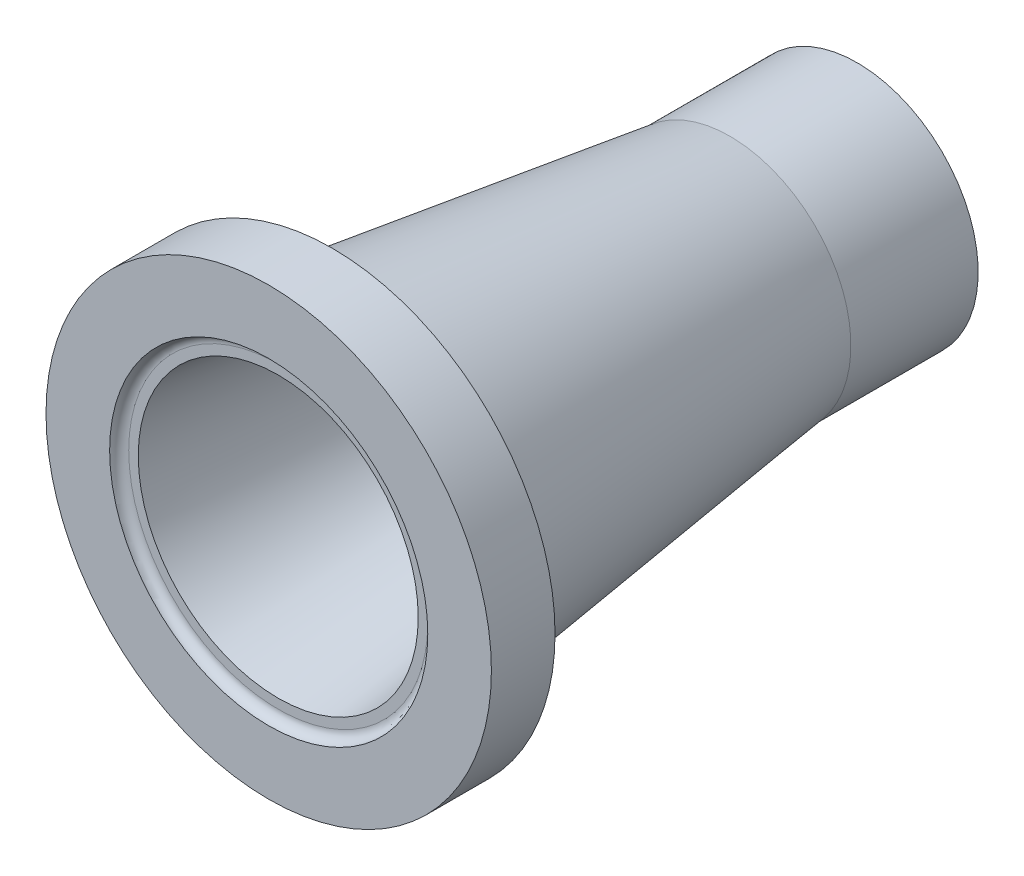
SolidWorks part; units mm, degrees
ref_plane "Front Plane" through (0, 0, 0) normal (0, 0, 1) x (1, 0, 0)
ref_plane "Top Plane" through (0, 0, 0) normal (0, 1, 0) x (1, 0, 0)
ref_plane "Right Plane" through (0, 0, 0) normal (1, 0, 0) x (0, 0, -1)
sketch "Sketch1" plane through (0, 0, 0) normal (0, 1, 0) x (1, 0, 0)
  line L0 (0, 195.7055) -> (0, -107.1066) construction
  line L2 (44, 3) -> (47, 3)
  line L3 (25, 185) -> (38, 185)
  line L4 (25, 185) -> (25, 145)
  line L5 (38, 185) -> (38, 145)
  line L6 (70, 0) -> (70, 20)
  line L7 (25, 145) -> (44, 3)
  line L8 (38, 145) -> (54.4932, 21.7348)
  line L9 (70, 20) -> (56.4756, 20)
  line L10 (50, 0) -> (70, 0)
  arc A0 (47, 3) -> (50, 0) centre (47, 0) cw
  arc A2 (56.4756, 20) -> (54.4932, 21.7348) centre (56.4756, 22) cw
  point P6 (-50, 0)
  point P7 (50, 0)
  point P16 (44, 3)
  point P17 (25, 185)
  dimension "D5" = 3
  dimension "D11" = 2
  dimension "D12" = 3
  dimension "D2" = 44
  dimension "D3" = 50
  dimension "D4" = 70
  dimension "D6" = 25
  dimension "D7" = 13
  dimension "D8" = 40
  dimension "D9" = 20
  dimension "D10" = 185
revolve "Revolve1" add sketch "Sketch1" angle 360 about L0
